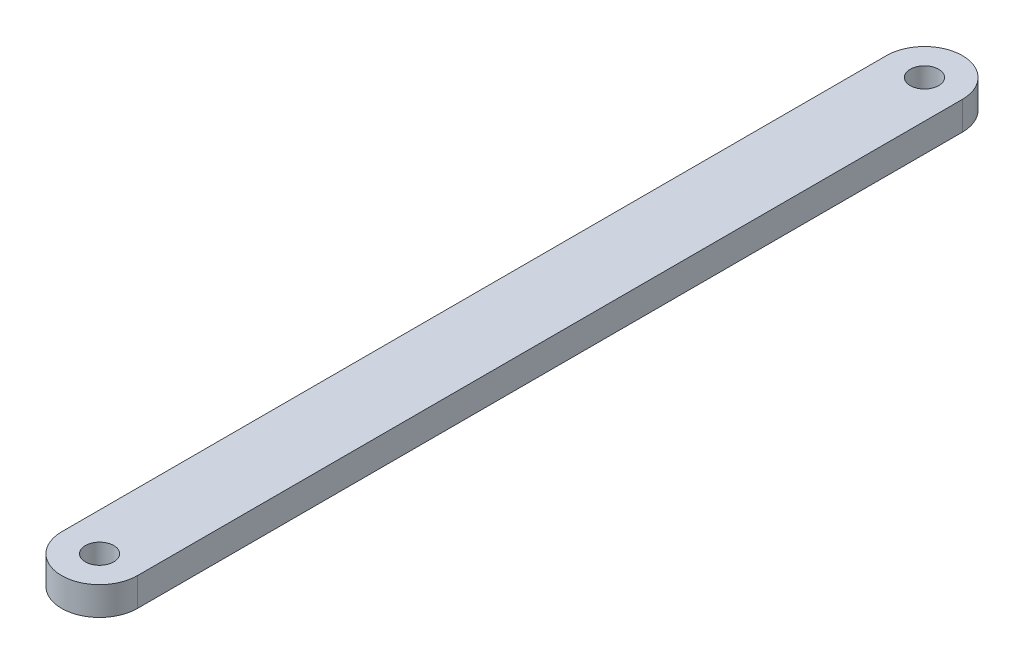
SolidWorks part; units mm, degrees
ref_plane "Alzado" through (0, 0, 0) normal (0, 0, 1) x (1, 0, 0)
ref_plane "Planta" through (0, 0, 0) normal (0, 1, 0) x (1, 0, 0)
ref_plane "Vista lateral" through (0, 0, 0) normal (1, 0, 0) x (0, 0, -1)
sketch "Croquis1" plane through (0, 0, 0) normal (0, 0, 1) x (1, 0, 0)
  line L0 (41840.1733, -436.9395) -> (41840.1733, -351.9395)
  line L1 (41832.1733, -351.9395) -> (41832.1733, -436.9395)
  line L2 (41840.1733, -436.9395) -> (41840.1733, -438.9395)
  line L4 (41832.1733, -436.9395) -> (41832.1733, -438.9395)
  circle A0 centre (41836.1733, -351.9395) radius 1.5
  arc A1 (41840.1733, -351.9395) -> (41832.1733, -351.9395) centre (41836.1733, -351.9395) ccw
  circle A4 centre (41836.1733, -438.9395) radius 1.5
  arc A5 (41832.1733, -438.9395) -> (41840.1733, -438.9395) centre (41836.1733, -438.9395) ccw
extrude "Saliente-Extruir1" add sketch "Croquis1" along normal blind 3
move or copy body "Sólido-Mover/Copiar1" bodies to move or copy 101 copy no rotation origin (0, -394.4395, 1.5) rotation axis (1, 0, 0) rotation angle 90
